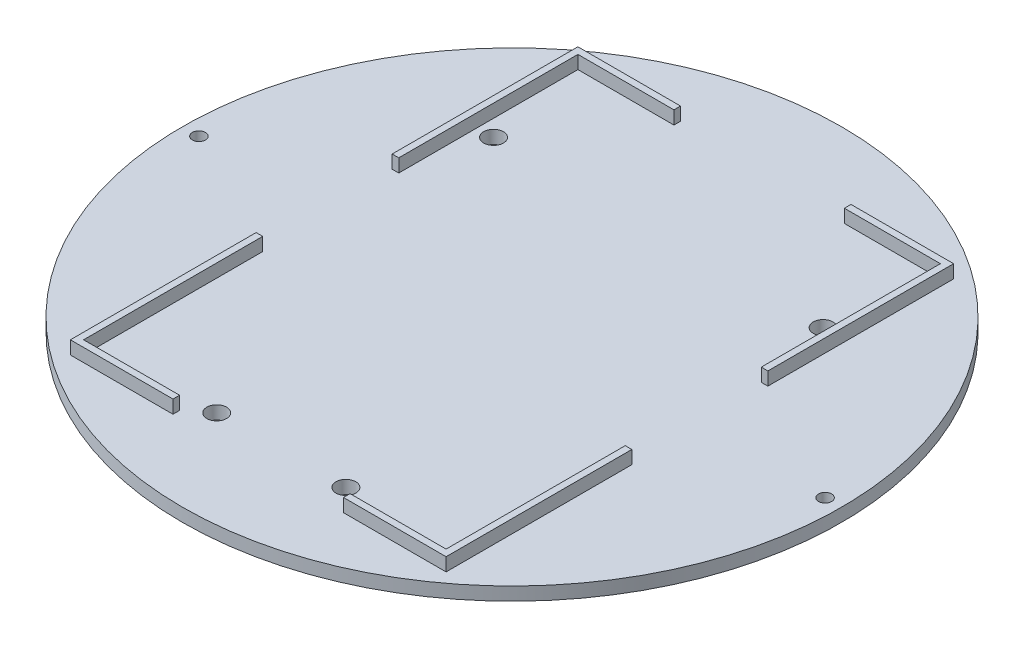
SolidWorks part; units mm, degrees
ref_plane "Front Plane" through (0, 0, 0) normal (0, 0, 1) x (1, 0, 0)
ref_plane "Top Plane" through (0, 0, 0) normal (0, 1, 0) x (1, 0, 0)
ref_plane "Right Plane" through (0, 0, 0) normal (1, 0, 0) x (0, 0, -1)
sketch "Sketch1" plane through (0, 0, 0) normal (0, 1, 0) x (1, 0, 0)
  circle A0 centre (0, 0) radius 50
  dimension "D1" = 100
extrude "Boss-Extrude3" add sketch "Sketch1" along normal blind 2
sketch "Sketch3" plane through (0, 2, 0) normal (0, 1, 0) x (1, 0, 0)
  line L0 (-28.5, 38.5) -> (28.5, 38.5)
  line L1 (-27.5, -37.5) -> (27.5, -37.5)
  line L2 (-27.5, -37.5) -> (-27.5, 37.5)
  line L3 (-27.5, 37.5) -> (27.5, 37.5)
  line L4 (27.5, -37.5) -> (27.5, 37.5)
  line L5 (-27.5, -37.5) -> (27.5, 37.5) construction
  line L6 (-27.5, 37.5) -> (27.5, -37.5) construction
  line L7 (28.5, -38.5) -> (28.5, 38.5)
  line L8 (-28.5, -38.5) -> (28.5, -38.5)
  line L9 (-28.5, -38.5) -> (-28.5, 38.5)
  point P0 (0, 0)
  dimension "D1" = 75
  dimension "D2" = 55
  dimension "D3" = 1
extrude "Boss-Extrude4" add sketch "Sketch3" along normal blind 2
sketch "Sketch4" plane through (0, 4, 0) normal (0, 1, 0) x (1, 0, 0)
  line L1 (-42.3669, 10.3209) -> (42.3669, 10.3209)
  line L2 (-42.3669, 10.3209) -> (-42.3669, -10.3209)
  line L3 (-42.3669, -10.3209) -> (42.3669, -10.3209)
  line L4 (42.3669, 10.3209) -> (42.3669, -10.3209)
  line L5 (-42.3669, 10.3209) -> (42.3669, -10.3209) construction
  line L6 (-42.3669, -10.3209) -> (42.3669, 10.3209) construction
  point P0 (0, 0)
extrude "Cut-Extrude1" cut sketch "Sketch4" against normal blind 2
sketch "Sketch5" plane through (0, 4, 0) normal (0, 1, 0) x (1, 0, 0)
  line L1 (-12.933, -47.0177) -> (12.933, -47.0177)
  line L2 (-12.933, -47.0177) -> (-12.933, 47.0177)
  line L3 (-12.933, 47.0177) -> (12.933, 47.0177)
  line L4 (12.933, -47.0177) -> (12.933, 47.0177)
  line L5 (-12.933, -47.0177) -> (12.933, 47.0177) construction
  line L6 (-12.933, 47.0177) -> (12.933, -47.0177) construction
  point P0 (0, 0)
extrude "Cut-Extrude2" cut sketch "Sketch5" against normal blind 2
sketch "Sketch6" plane through (0, 2, 0) normal (0, 1, 0) x (1, 0, 0)
  line L0 (27.5, 37.5) -> (12.933, 37.5) construction
  line L1 (27.5, 10.3209) -> (27.5, 37.5) construction
  line L2 (0, 50) -> (0, -50) construction
  line L3 (27.5, -37.5) -> (27.5, -10.3209) construction
  line L4 (12.933, -37.5) -> (27.5, -37.5) construction
  circle A0 centre (25, 22.2) radius 1.5
  circle A1 centre (0, 0) radius 50 construction
  circle A2 centre (-25, 22.2) radius 1.5
  circle A3 centre (9.8, -35) radius 1.5
  circle A4 centre (-9.8, -35) radius 1.5
  dimension "D2" = 2.5
  dimension "D3" = 3
  dimension "D5" = 3
  dimension "D6" = 2.5
  dimension "D1" = 15.3
  dimension "D4" = 17.7
extrude "Cut-Extrude3" cut sketch "Sketch6" against normal blind 12
sketch "Sketch7" plane through (0, 2, 0) normal (0, 1, 0) x (1, 0, 0)
  circle A1 centre (-47.5, 0) radius 1
  circle A2 centre (47.5, 0) radius 1
  dimension "D2" = 2
  dimension "D1" = 47.5
extrude "Cut-Extrude4" cut sketch "Sketch7" against normal blind 10.15
